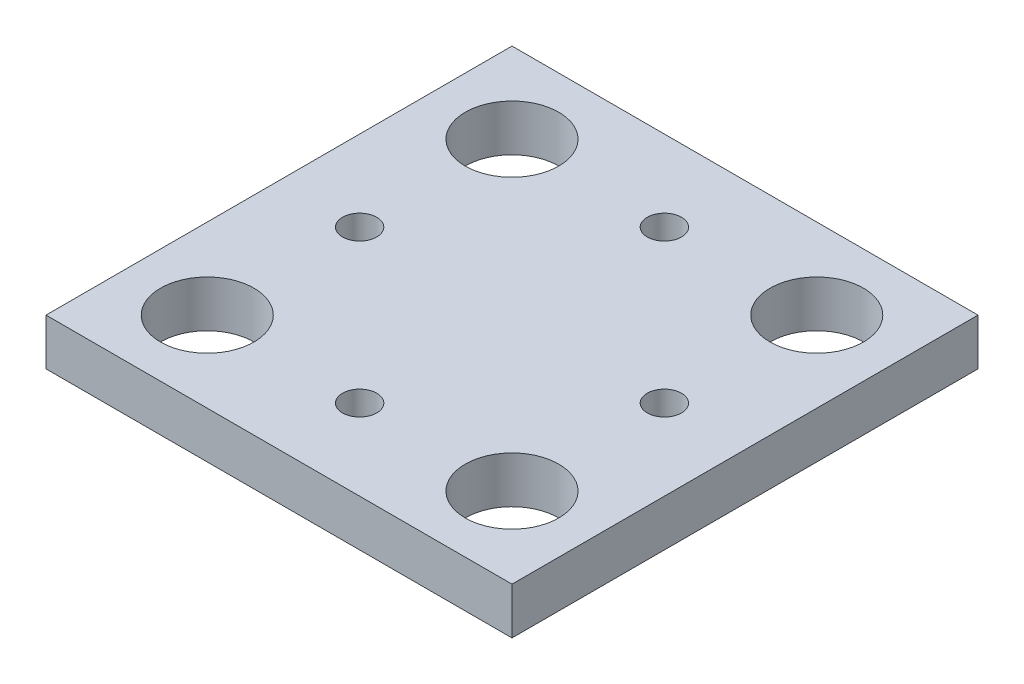
SolidWorks part; units mm, degrees
material "polylactic acid(PLA)(20%)"
ref_plane "Front Plane" through (0, 0, 0) normal (0, 0, 1) x (1, 0, 0)
ref_plane "Top Plane" through (0, 0, 0) normal (0, 1, 0) x (1, 0, 0)
ref_plane "Right Plane" through (0, 0, 0) normal (1, 0, 0) x (0, 0, -1)
sketch "Sketch1" plane through (0, 0, 0) normal (0, 1, 0) x (1, 0, 0)
  line L1 (-50, 50) -> (50, 50)
  line L2 (-50, 50) -> (-50, -50)
  line L3 (-50, -50) -> (50, -50)
  line L4 (50, 50) -> (50, -50)
  point P4 (50, 0)
  point P7 (0, -50)
  dimension "D1" = 100
extrude "Boss-Extrude1" add sketch "Sketch1" along normal blind 10
sketch "Sketch3" plane through (0, 0, 0) normal (0, 1, 0) x (1, 0, 0)
  line L0 (50, 50) -> (-50, 50) construction
  line L1 (-50, 50) -> (-50, -50) construction
  circle A0 centre (-32.7, 32.7) radius 10.025
  circle A1 centre (32.7, 32.7) radius 10.025
  circle A2 centre (32.7, -32.7) radius 10.025
  circle A3 centre (-32.7, -32.7) radius 10.025
  circle A4 centre (-32.7, 32.7) radius 17.3 construction
  circle A5 centre (-32.7, -32.7) radius 17.3 construction
  circle A6 centre (32.7, 32.7) radius 17.3 construction
  circle A7 centre (0, 32.7) radius 3.675
  circle A8 centre (0, 32.7) radius 7.5 construction
  circle A9 centre (32.7, 0) radius 3.675
  circle A10 centre (0, -32.7) radius 3.675
  circle A11 centre (-32.7, 0) radius 3.675
  point P14 (0, 0)
  point P29 (0, 0)
  dimension "D1" = 20.05
  dimension "D2" = 34.6
  dimension "D4" = 7.35
  dimension "D5" = 15
  dimension "D3" = 4
  dimension "D6" = 4
extrude "Cut-Extrude3" cut sketch "Sketch3" against normal through all and the other way through all
